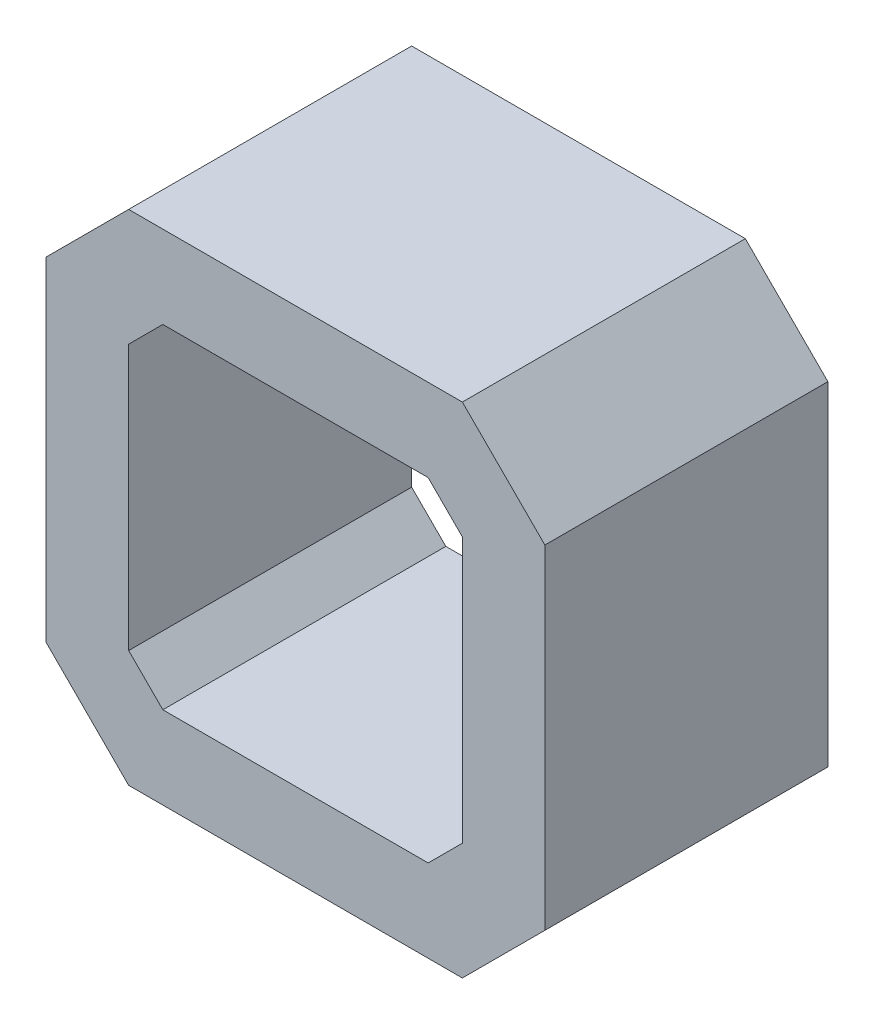
SolidWorks part; units mm, degrees
material "Acero aleado"
ref_plane "Alzado" through (0, 0, 0) normal (0, 0, 1) x (1, 0, 0)
ref_plane "Planta" through (0, 0, 0) normal (0, 1, 0) x (1, 0, 0)
ref_plane "Vista lateral" through (0, 0, 0) normal (1, 0, 0) x (0, 0, -1)
sketch "Croquis1" plane through (0, 0, 0) normal (0, 0, 1) x (1, 0, 0)
  line L0 (-14.15, 21.15) -> (-21.15, 14.15)
  line L1 (-14.15, 21.15) -> (14.15, 21.15)
  line L2 (-21.15, 14.15) -> (-21.15, -14.15)
  line L3 (-14.15, -21.15) -> (14.15, -21.15)
  line L4 (21.15, 14.15) -> (21.15, -14.15)
  line L5 (-21.15, 21.15) -> (21.15, -21.15) construction
  line L6 (-21.15, -21.15) -> (21.15, 21.15) construction
  line L7 (14.15, 21.15) -> (21.15, 14.15)
  line L8 (21.15, -14.15) -> (14.15, -21.15)
  line L9 (-21.15, -14.15) -> (-14.15, -21.15)
  point P0 (0, 0)
  dimension "D1" = 42.3
  dimension "D2" = 42.3
extrude "Saliente-Extruir1" add sketch "Croquis1" along normal blind 24
shell "Shell1" thickness 7
